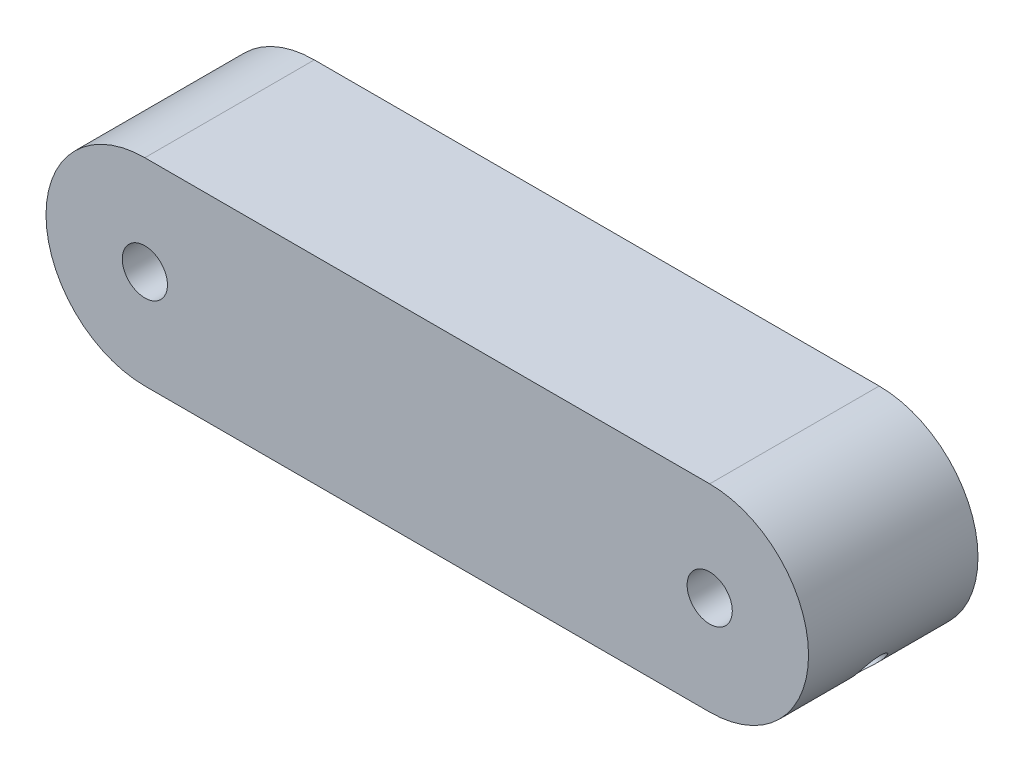
SolidWorks part; units mm, degrees
material "ABS"
ref_plane "Alzado" through (0, 0, 0) normal (0, 0, 1) x (1, 0, 0)
ref_plane "Planta" through (0, 0, 0) normal (0, 1, 0) x (1, 0, 0)
ref_plane "Vista lateral" through (0, 0, 0) normal (1, 0, 0) x (0, 0, -1)
sketch "Sketch1" plane through (0, 0, 0) normal (0, 0, 1) x (1, 0, 0)
  line L0 (0, 0) -> (40, 0) construction
  line L1 (0, 7) -> (40, 7)
  line L2 (0, -7) -> (40, -7)
  arc A0 (0, 7) -> (0, -7) centre (0, 0) ccw
  arc A1 (40, -7) -> (40, 7) centre (40, 0) ccw
  point P3 (20, 0)
  point P8 (0, 0)
extrude "Boss-Extrude1" add sketch "Sketch1" along normal mid plane 12
sketch "Sketch2" plane through (0, 0, 6) normal (0, 0, 1) x (1, 0, 0)
  circle A0 centre (0, 0) radius 1.6
  circle A1 centre (40, 0) radius 1.6
extrude "Cut-Extrude1" cut sketch "Sketch2" against normal through all
sketch "Sketch3" plane through (0, 0, 0) normal (1, 0, 0) x (0, 0, -1)
  circle A0 centre (0, -4.5) radius 1
extrude "Cut-Extrude2" cut sketch "Sketch3" against normal mid plane 120
